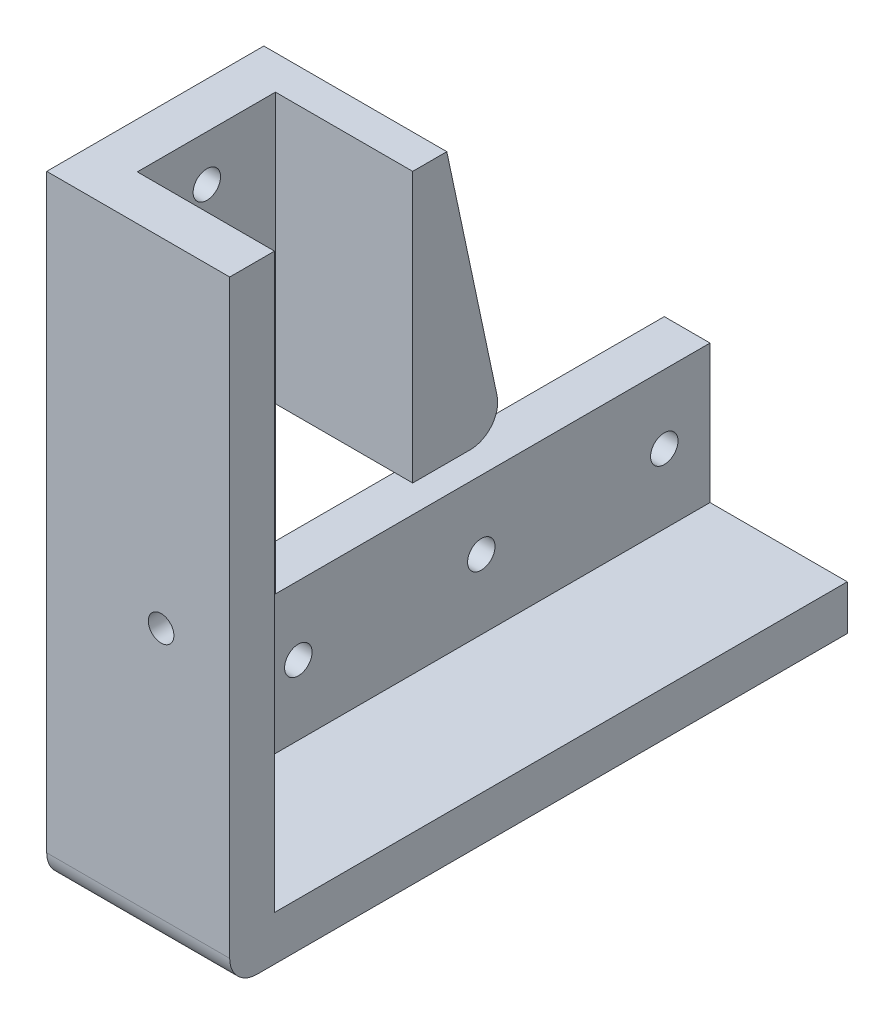
SolidWorks part; units mm, degrees
material "PLA"
ref_plane "前视基准面" through (0, 0, 0) normal (0, 0, 1) x (1, 0, 0)
ref_plane "上视基准面" through (0, 0, 0) normal (0, 1, 0) x (1, 0, 0)
ref_plane "右视基准面" through (0, 0, 0) normal (1, 0, 0) x (0, 0, -1)
sketch "草图1" plane through (0, 0, 0) normal (1, 0, 0) x (0, 0, -1)
  line L0 (0, 0) -> (0, 55) construction
  line L1 (0, 0) -> (55, 0) construction
  line L2 (7.5, 7.5) -> (55, 7.5) construction
  line L3 (7.5, 7.5) -> (7.5, 55) construction
  line L4 (-7.5, -7.5) -> (55, -7.5) construction
  line L5 (-7.5, -7.5) -> (-7.5, 55) construction
  line L6 (-12.5, -12.5) -> (55, -12.5)
  line L7 (-12.5, -12.5) -> (-12.5, 55)
  line L8 (55, 7.5) -> (7.5, 7.5)
  line L9 (7.5, 7.5) -> (7.5, 25.5)
  line L10 (7.5, 25.5) -> (17.5, 25.5)
  line L11 (17.5, 25.5) -> (11.2296, 55)
  line L12 (11.2296, 55) -> (-12.5, 55)
  line L13 (55, -12.5) -> (55, 7.5)
  line L14 (-7.5, -7.5) -> (0, 0) construction
  circle A0 centre (0, 10) radius 1.5
  circle A1 centre (0, 30) radius 1.5
  circle A2 centre (10, 0) radius 1.5
  circle A3 centre (30, 0) radius 1.5
  circle A4 centre (50, 0) radius 1.5
  circle A5 centre (0, 50) radius 1.5
  dimension "D8" = 20
  dimension "D9" = 10
  dimension "D10" = 20
  dimension "D11" = 3
  dimension "D4" = 18
  dimension "D5" = 10
  dimension "D6" = 55
  dimension "D7" = 55
  dimension "D12" = 12
  dimension "D1" = 7.5
  dimension "D2" = 7.5
  dimension "D3" = 5
extrude "凸台-拉伸1" add sketch "草图1" along normal blind 20
sketch "草图2" plane through (20, 0, 0) normal (-1, 0, 0) x (0, 0, 1)
  line L0 (7.6, 55) -> (7.6, -7.6)
  line L1 (-11.2296, 55) -> (12.5, 55) construction
  line L2 (7.6, -7.6) -> (-55, -7.6)
  line L3 (-55, -12.5) -> (-55, 7.5) construction
  line L4 (-55, -7.6) -> (-55, 7.5)
  line L5 (-55, 7.5) -> (-7.5, 7.5)
  line L6 (-7.5, 7.5) -> (-7.5, 55)
  line L7 (-7.5, 55) -> (7.6, 55)
  dimension "D1" = 15.1
  dimension "D2" = 15.1
extrude "切除-拉伸1" cut sketch "草图2" along normal blind 15
sketch "草图3" plane through (0, 0, 7.6) normal (0, 0, -1) x (-1, 0, 0)
  line L2 (-20, -7.6) -> (-20, 55) construction
  circle A0 centre (-12.5, 18) radius 1.4
  dimension "D1" = 18
  dimension "D2" = 7.5
  dimension "D3" = 2.8
extrude "切除-拉伸2" cut sketch "草图3" against normal through all
fillet "圆角1" radius 3 2 edges at (10, 25.5, -17.5) (10, -12.5, 12.5)
